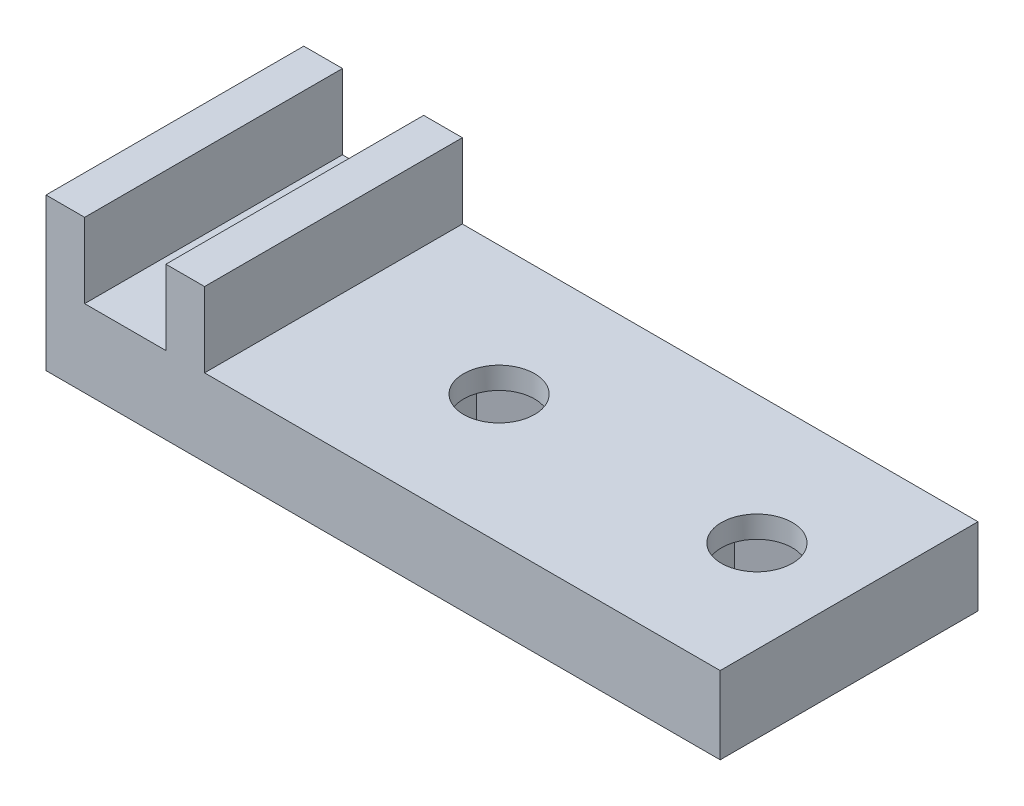
SolidWorks part; units mm, degrees
ref_plane "Спереди" through (0, 0, 0) normal (0, 0, 1) x (1, 0, 0)
ref_plane "Сверху" through (0, 0, 0) normal (0, 1, 0) x (1, 0, 0)
ref_plane "Справа" through (0, 0, 0) normal (1, 0, 0) x (0, 0, -1)
other "Configuration Table"
sketch "Профиль_скобы_6мм" plane through (0, 0, 0) normal (0, 0, 1) x (1, 0, 0)
  line L0 (-3.15, -6) -> (49.15, -6)
  line L1 (49.15, -6) -> (49.15, 0)
  line L2 (49.15, 0) -> (9.15, 0)
  line L3 (9.15, 0) -> (9.15, 5.8)
  line L4 (9.15, 5.8) -> (6.15, 5.8)
  line L5 (6.15, 5.8) -> (6.15, 0)
  line L6 (6.15, 0) -> (-0.15, 0)
  line L7 (-0.15, 0) -> (-0.15, 5.8)
  line L8 (-0.15, 5.8) -> (-3.15, 5.8)
  line L9 (-3.15, 5.8) -> (-3.15, -6)
  dimension "X001" = 3.15
  dimension "X002" = 0.15
  dimension "X003" = 6.15
  dimension "X004" = 9.15
  dimension "X005" = 49.15
  dimension "Y001" = 6
  dimension "Y002" = 5.8
extrude "Печатный_корпус_20мм" add sketch "Профиль_скобы_6мм" along normal blind 20
sketch "Винты_полки_М5_эскиз" plane through (0, 0, 0) normal (0, 1, 0) x (1, 0, 0)
  circle A0 centre (22, -10) radius 2.75
  circle A1 centre (42, -10) radius 2.75
  dimension "Диаметр001" = 5.5
  dimension "Диаметр002" = 5.5
  dimension "X001" = 22
  dimension "X002" = 42
  dimension "Y001" = 10
extrude "Винты_полки_М5" cut sketch "Винты_полки_М5_эскиз" against normal through all and the other way through all
sketch "Гайки_полки_М5_эскиз" plane through (0, -6, 0) normal (0, -1, 0) x (1, 0, 0)
  line L0 (22, 14.792) -> (26.15, 12.396)
  line L1 (26.15, 12.396) -> (26.15, 7.604)
  line L2 (26.15, 7.604) -> (22, 5.208)
  line L3 (22, 5.208) -> (17.85, 7.604)
  line L4 (17.85, 7.604) -> (17.85, 12.396)
  line L5 (17.85, 12.396) -> (22, 14.792)
  line L6 (42, 14.792) -> (46.15, 12.396)
  line L7 (46.15, 12.396) -> (46.15, 7.604)
  line L8 (46.15, 7.604) -> (42, 5.208)
  line L9 (42, 5.208) -> (37.85, 7.604)
  line L10 (37.85, 7.604) -> (37.85, 12.396)
  line L11 (37.85, 12.396) -> (42, 14.792)
  dimension "X001" = 17.85
  dimension "X002" = 22
  dimension "X003" = 26.15
  dimension "X004" = 37.85
  dimension "X005" = 42
  dimension "X006" = 46.15
  dimension "Y001" = 5.208
  dimension "Y002" = 7.604
  dimension "Y003" = 12.396
  dimension "Y004" = 14.792
extrude "Гайки_полки_М5_4_3мм" cut sketch "Гайки_полки_М5_эскиз" against normal blind 4.3
